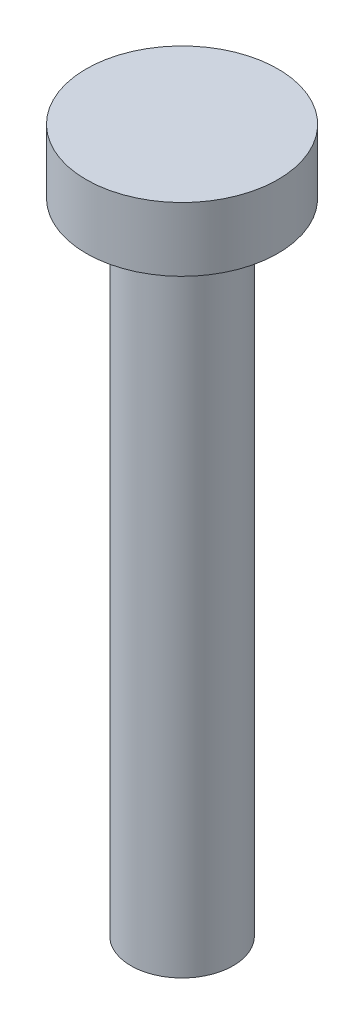
SolidWorks part; units mm, degrees
ref_plane "前视基准面" through (0, 0, 0) normal (0, 0, 1) x (1, 0, 0)
ref_plane "上视基准面" through (0, 0, 0) normal (0, 1, 0) x (1, 0, 0)
ref_plane "右视基准面" through (0, 0, 0) normal (1, 0, 0) x (0, 0, -1)
sketch "草图1" plane through (0, 0, 0) normal (0, 1, 0) x (1, 0, 0)
  line L0 (0, 0) -> (50000, 0) construction
  line L1 (0, 0) -> (0, 50000) construction
  circle A0 centre (0, 0) radius 8
extrude "凸台-拉伸1" add sketch "草图1" along normal blind 100 contours A0
sketch "草图2" plane through (0, 100, 0) normal (0, 1, 0) x (1, 0, 0)
  circle A0 centre (0, 0) radius 15
extrude "凸台-拉伸2" add sketch "草图2" along normal blind 10
